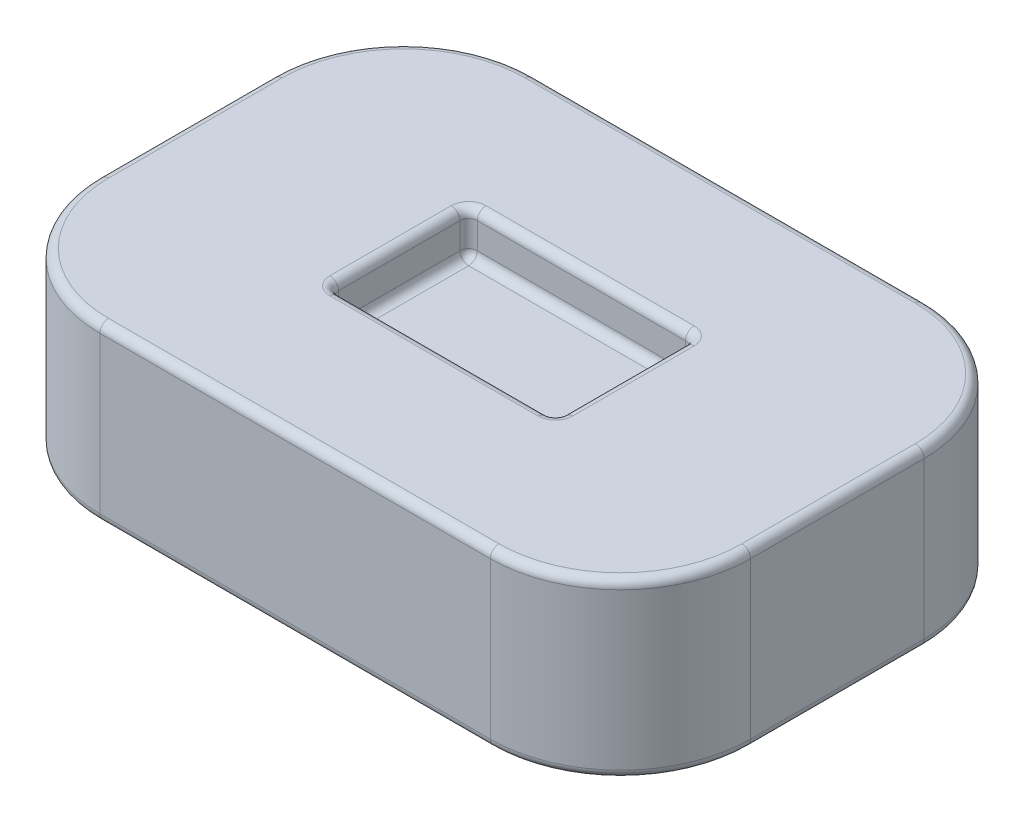
SolidWorks part; units mm, degrees
ref_plane "Front Plane" through (0, 0, 0) normal (0, 0, 1) x (1, 0, 0)
ref_plane "Top Plane" through (0, 0, 0) normal (0, 1, 0) x (1, 0, 0)
ref_plane "Right Plane" through (0, 0, 0) normal (1, 0, 0) x (0, 0, -1)
sketch "Sketch1" plane through (0, 0, 0) normal (0, 1, 0) x (1, 0, 0)
  line L1 (-7.5, 5) -> (7.5, 5)
  line L2 (-7.5, 5) -> (-7.5, -5)
  line L3 (-7.5, -5) -> (7.5, -5)
  line L4 (7.5, 5) -> (7.5, -5)
  line L5 (-7.5, 5) -> (7.5, -5) construction
  line L6 (-7.5, -5) -> (7.5, 5) construction
  point P0 (0, 0)
  dimension "D1" = 10
  dimension "D2" = 15
extrude "Boss-Extrude1" add sketch "Sketch1" along normal blind 4
sketch "Sketch2" plane through (0, 4, 0) normal (0, 1, 0) x (1, 0, 0)
  line L1 (-2.6, 1.6) -> (2.6, 1.6)
  line L2 (-2.6, 1.6) -> (-2.6, -1.6)
  line L3 (-2.6, -1.6) -> (2.6, -1.6)
  line L4 (2.6, 1.6) -> (2.6, -1.6)
  line L5 (-2.6, 1.6) -> (2.6, -1.6) construction
  line L6 (-2.6, -1.6) -> (2.6, 1.6) construction
  point P0 (0, 0)
  dimension "D1" = 3.2
  dimension "D2" = 5.2
extrude "Cut-Extrude1" cut sketch "Sketch2" against normal blind 1
fillet "Fillet1" radius 3 4 edges at (-7.5, 2, -5) (7.5, 2, -5) (-7.5, 2, 5) (7.5, 2, 5)
fillet "Fillet2" radius 0.2 28 edges at (0, 3, -1.6) (2.6, 3, 0) (2.6, 3.5, -1.6) (0, 3, 1.6) (2.6, 3.5, 1.6) (-2.6, 3.5, -1.6) (-2.6, 3, 0) (-2.6, 3.5, 1.6) (-6.6213, 0, 4.1213) (0, 0, 5) (6.6213, 0, 4.1213) (7.5, 0, 0) (6.6213, 0, -4.1213) (0, 0, -5) (-6.6213, 0, -4.1213) (-7.5, 0, 0) (6.6213, 4, -4.1213) (7.5, 4, 0) (6.6213, 4, 4.1213) (0, 4, 5) (-6.6213, 4, 4.1213) (-7.5, 4, 0) (-6.6213, 4, -4.1213) (0, 4, -5) (0, 4, -1.6) (-2.6, 4, 0) (0, 4, 1.6) (2.6, 4, 0)
